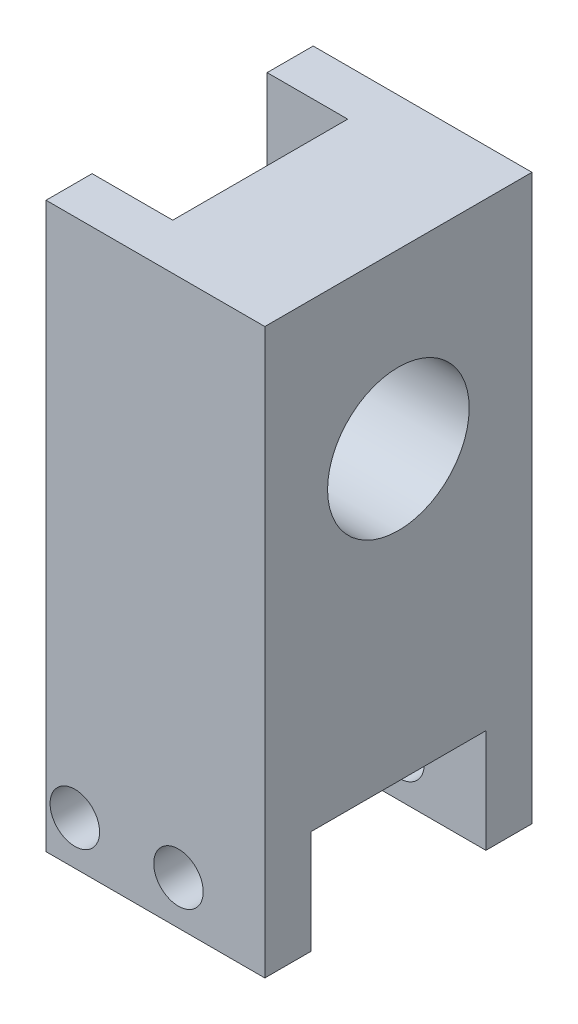
SolidWorks part; units mm, degrees
ref_plane "Front Plane" through (0, 0, 0) normal (0, 0, 1) x (1, 0, 0)
ref_plane "Top Plane" through (0, 0, 0) normal (0, 1, 0) x (1, 0, 0)
ref_plane "Right Plane" through (0, 0, 0) normal (1, 0, 0) x (0, 0, -1)
sketch "Sketch1" plane through (0, 0, 0) normal (0, 0, 1) x (1, 0, 0)
  line L0 (65, 44) -> (77, 44)
  line L1 (77, 44) -> (77, 84)
  line L2 (77, 84) -> (65, 84)
  line L3 (65, 84) -> (65, 44)
extrude "Guided bridge with rod coupling seat" add sketch "Sketch1" along normal blind 23.2 from offset 38.4
sketch "Sketch2" plane through (0, 0, 0) normal (0, 0, 1) x (1, 0, 0)
  line L0 (58, 35) -> (77, 35)
  line L1 (77, 35) -> (77, 84)
  line L2 (77, 84) -> (58, 84)
  line L3 (58, 84) -> (58, 35)
extrude "Lower rack lap" add sketch "Sketch2" along normal blind 4 from offset 38.4
sketch "Sketch3" plane through (0, 0, 0) normal (0, 0, 1) x (1, 0, 0)
  line L0 (58, 35) -> (77, 35)
  line L1 (77, 35) -> (77, 84)
  line L2 (77, 84) -> (58, 84)
  line L3 (58, 84) -> (58, 35)
extrude "Upper rack lap" add sketch "Sketch3" along normal blind 4 from offset 57.6
sketch "Sketch4" plane through (0, 0, 0) normal (0, 0, 1) x (1, 0, 0)
  circle A0 centre (60.5, 38.8) radius 2.15
  circle A1 centre (69.5, 38.8) radius 2.15
extrude "M4 joint bolt clearance" cut sketch "Sketch4" along normal blind 23.2 from offset 38.4
sketch "Sketch5" plane through (0, 0, 0) normal (1, 0, 0) x (0, 0, -1)
  circle A0 centre (-50, 69) radius 6.15
extrude "Radial floating stud clearance" cut sketch "Sketch5" along normal blind 12 from offset 65
